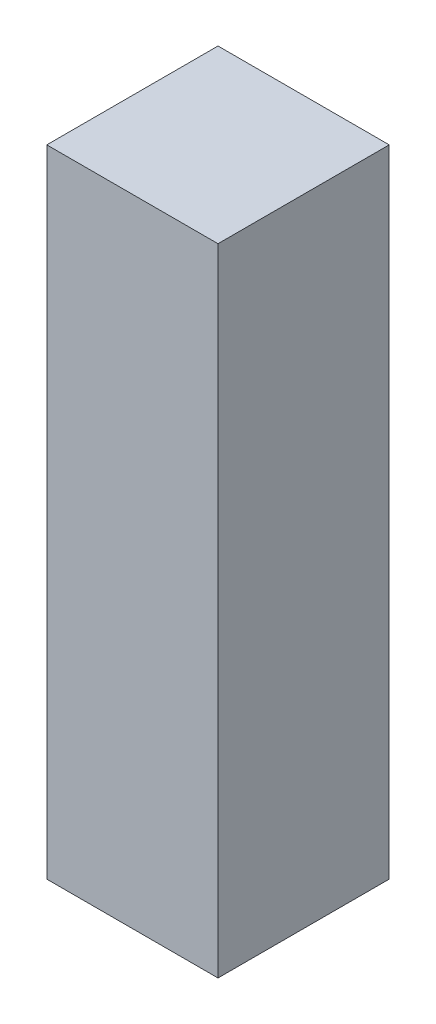
SolidWorks part; units mm, degrees
material "Pine"
ref_plane "Front Plane" through (0, 0, 0) normal (0, 0, 1) x (1, 0, 0)
ref_plane "Top Plane" through (0, 0, 0) normal (0, 1, 0) x (1, 0, 0)
ref_plane "Right Plane" through (0, 0, 0) normal (1, 0, 0) x (0, 0, -1)
sketch "Sketch1" plane through (0, 0, 0) normal (0, 1, 0) x (1, 0, 0)
  line L1 (0, 0) -> (88.9, 0)
  line L2 (0, 0) -> (0, 88.9)
  line L3 (0, 88.9) -> (88.9, 88.9)
  line L4 (88.9, 0) -> (88.9, 88.9)
  dimension "D1" = 88.9
extrude "Boss-Extrude1" add sketch "Sketch1" along normal blind 330.2 contours L2 L1 L4 L3
